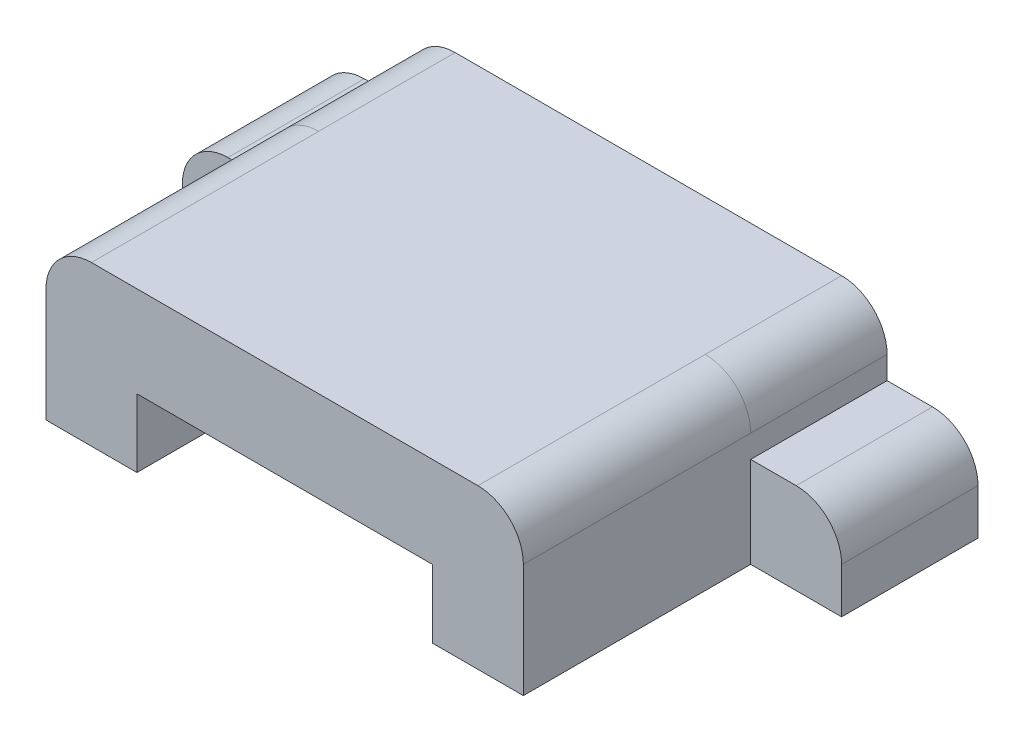
SolidWorks part; units mm, degrees
ref_plane "Front Plane" through (0, 0, 0) normal (0, 0, 1) x (1, 0, 0)
ref_plane "Top Plane" through (0, 0, 0) normal (0, 1, 0) x (1, 0, 0)
ref_plane "Right Plane" through (0, 0, 0) normal (1, 0, 0) x (0, 0, -1)
sketch "Sketch1" plane through (0, 0, 0) normal (0, 0, 1) x (1, 0, 0)
  line L0 (-16.4615, -8.7436) -> (-8.4615, -8.7436)
  line L1 (-8.4615, -5.7436) -> (-8.4615, -8.7436)
  line L2 (-8.4615, -5.7436) -> (4.5385, -5.7436)
  line L3 (4.5385, -5.7436) -> (4.5385, -8.7436)
  line L4 (4.5385, -8.7436) -> (12.5385, -8.7436)
  line L5 (-16.4615, -8.7436) -> (-16.4615, -4.7436)
  line L6 (-16.4615, -4.7436) -> (-12.4615, -4.7436)
  line L7 (-12.4615, -4.7436) -> (-12.4615, -1.7436)
  line L8 (-12.4615, -1.7436) -> (8.5385, -1.7436)
  line L9 (8.5385, -1.7436) -> (8.5385, -4.7436)
  line L10 (8.5385, -4.7436) -> (12.5385, -4.7436)
  line L11 (12.5385, -4.7436) -> (12.5385, -8.7436)
  dimension "D1" = 13
  dimension "D2" = 3
  dimension "D3" = 3
  dimension "D4" = 8
  dimension "D5" = 8
  dimension "D6" = 4
  dimension "D7" = 4
  dimension "D8" = 4
  dimension "D9" = 4
  dimension "D10" = 4
extrude "Boss-Extrude1" add sketch "Sketch1" along normal blind 6
fillet "Fillet1" radius 2 4 edges at (-16.4615, -4.7436, 3) (12.5385, -4.7436, 3) (-12.4615, -1.7436, 3) (8.5385, -1.7436, 3)
sketch "Sketch3" plane through (0, 0, 6) normal (0, 0, 1) x (1, 0, 0)
  line L0 (-8.4615, -5.7436) -> (-8.4615, -8.7436)
  line L1 (-12.4615, -4.7436) -> (-12.4615, -8.7436)
  line L2 (-16.4615, -8.7436) -> (-8.4615, -8.7436) construction
  line L3 (-12.4615, -8.7436) -> (-8.4615, -8.7436)
  line L4 (-8.4615, -5.7436) -> (4.5385, -5.7436)
  line L5 (4.5385, -5.7436) -> (4.5385, -8.7436)
  line L6 (4.5385, -8.7436) -> (12.5385, -8.7436) construction
  line L7 (4.5385, -5.7436) -> (4.5385, -8.7436) construction
  line L9 (8.5385, -4.7436) -> (8.5385, -8.7436)
  line L10 (8.5385, -8.7436) -> (4.5385, -8.7436)
  line L11 (-10.4615, -1.7436) -> (-12.4615, -1.7436)
  line L12 (-12.4615, -1.7436) -> (-12.4615, -4.7436)
  line L13 (-10.4615, -1.7436) -> (8.5385, -1.7436)
  line L14 (8.5385, -1.7436) -> (8.5385, -4.7436)
extrude "Boss-Extrude2" add sketch "Sketch3" along normal blind 10
fillet "Fillet2" radius 2 2 edges at (8.5385, -1.7436, 11) (-12.4615, -1.7436, 11)
